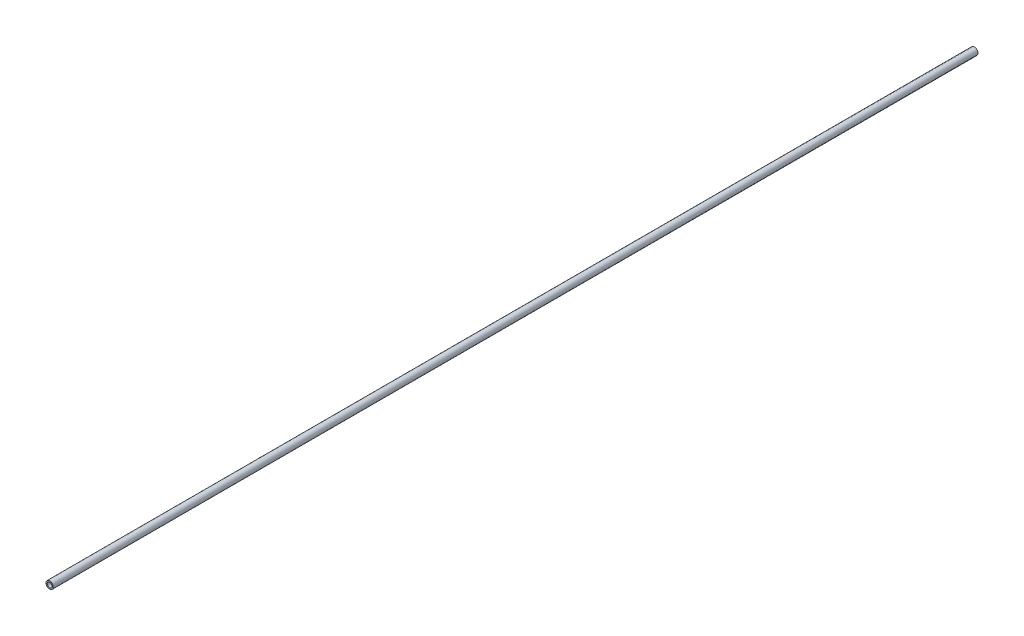
SolidWorks part; units mm, degrees
material "Wing Spar Carbon Fiber"
ref_plane "Front Plane" through (0, 0, 0) normal (0, 0, 1) x (1, 0, 0)
ref_plane "Top Plane" through (0, 0, 0) normal (0, 1, 0) x (1, 0, 0)
ref_plane "Right Plane" through (0, 0, 0) normal (1, 0, 0) x (0, 0, -1)
sketch "Sketch1" plane through (0, 0, 0) normal (0, 0, 1) x (1, 0, 0)
  circle A0 centre (0, 0) radius 4.7625
  circle A1 centre (0, 0) radius 3.175
  dimension "D1" = 9.525
  dimension "D2" = 6.35
extrude "Boss-Extrude1" add sketch "Sketch1" along normal blind 1219.2
equation "\"D1@Boss-Extrude1\"=\"wing_spar_l\""
equation "\"D1@Sketch1\"=\"wing_spar_d\""
equation "\"span\"= 48"
equation "\"wing_chord\"= 9"
equation "\"fuse_len\"= 15"
equation "\"fuse_height\"= 5"
equation "\"fuse_wid\"= 5"
equation "\"foam_t\"= 0.1875"
equation "\"main_spar_len\"= 36"
equation "\"x_fuse_to_wing\"= 3"
equation "\"x_cg_from_le\"= 2.25"
equation "\"boom_len\"= 30"
equation "\"wing_angle\"= 1.5"
equation "\"boom_d\"= 0.75"
equation "\"wing_spar_d\"= 0.375"
equation "\"wing_spar_l\"= 48"
equation "\"wing_spar_spacing\"= 1.35"
equation "\"wing_mount_l\"= 2.5"
equation "\"boom_mount_l\"= 1"
equation "\"vstab_span\"= 6.5"
equation "\"hstab_span\"= 15.25"
equation "\"tail_chord\"= 5"
equation "\"wing_spar_ID\"= 0.25"
equation "\"fuse_inner_arc_length\" = 0.5"
equation "\"fuse_inner_r\" = \"fuse_inner_arc_length\" * 4 / (2*pi)"
equation "\"fuse_outer_r\" = \"fuse_inner_r\" + \"foam_t\""
equation "\"wing_mount_bolt_spacing\" = \"wing_mount_l\" * 0.5"
equation "\"fuse_inner_h\" = \"fuse_height\" - 2 * \"foam_t\""
equation "\"fuse_inner_w\" = \"fuse_wid\" - 2 * \"fuse_outer_r\""
equation "\"D2@Sketch1\"= \"wing_spar_ID\""
